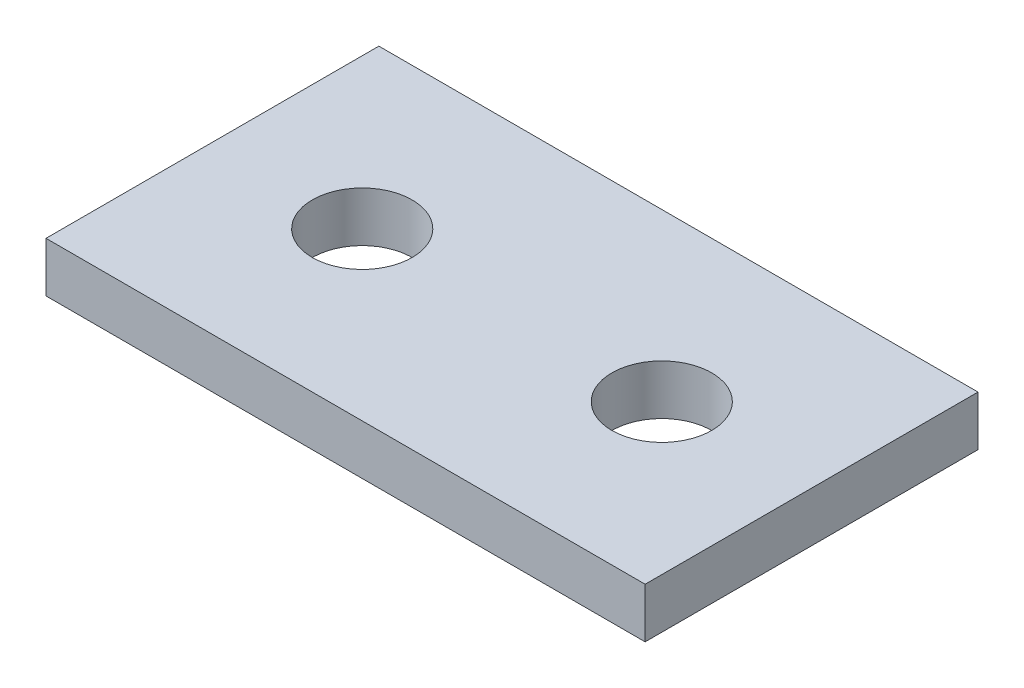
SolidWorks part; units mm, degrees
ref_plane "Alzado" through (0, 0, 0) normal (0, 0, 1) x (1, 0, 0)
ref_plane "Planta" through (0, 0, 0) normal (0, 1, 0) x (1, 0, 0)
ref_plane "Vista lateral" through (0, 0, 0) normal (1, 0, 0) x (0, 0, -1)
sketch "Croquis2" plane through (0, 0, 0) normal (0, 1, 0) x (1, 0, 0)
  line L1 (0, 0) -> (114.3, 0)
  line L2 (0, 0) -> (0, -63.5)
  line L3 (0, -63.5) -> (114.3, -63.5)
  line L4 (114.3, 0) -> (114.3, -63.5)
  dimension "D1" = 63.5
  dimension "D2" = 114.3
extrude "Saliente-Extruir1" add sketch "Croquis2" along normal blind 9.525
sketch "Croquis3" plane through (0, 9.525, 0) normal (0, 1, 0) x (1, 0, 0)
  line L0 (57.15, 0) -> (57.15, -31.75) construction
  line L2 (114.3, 0) -> (0, 0) construction
  line L3 (57.15, -31.75) -> (0, -31.75) construction
  line L4 (0, 0) -> (0, -63.5) construction
  circle A0 centre (28.575, -31.75) radius 9.525
  circle A1 centre (85.725, -31.75) radius 9.525
  dimension "D1" = 19.05
extrude "Cortar-Extruir1" cut sketch "Croquis3" against normal blind 9.525
